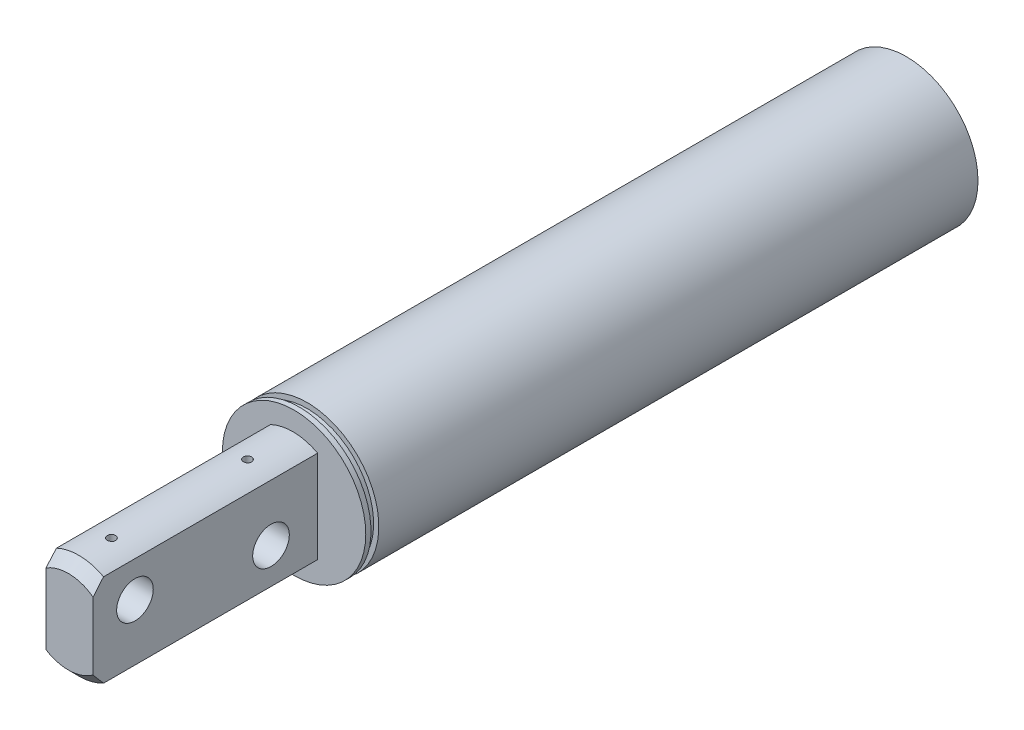
SolidWorks part; units mm, degrees
material "1060 合金"
ref_plane "前视基准面" through (0, 0, 0) normal (0, 0, 1) x (1, 0, 0)
ref_plane "上视基准面" through (0, 0, 0) normal (0, 1, 0) x (1, 0, 0)
ref_plane "右视基准面" through (0, 0, 0) normal (1, 0, 0) x (0, 0, -1)
sketch "草图1" plane through (0, 0, 0) normal (0, 0, 1) x (1, 0, 0)
  circle A0 centre (0, 0) radius 13.7
  dimension "D1" = 27.4
extrude "凸台-拉伸1" add sketch "草图1" along normal blind 117
sketch "草图6" plane through (0, 0, 0) normal (0, 1, 0) x (1, 0, 0)
  line L0 (0, 0) -> (0, -36.1312) construction
  line L1 (-13.7, 0) -> (-13.7, -117) construction
  line L2 (-13.7, -116) -> (-12.7, -116)
  line L3 (-13.7, -116) -> (-13.7, -114.5)
  line L4 (-13.7, -114.5) -> (-12.7, -114.5)
  line L5 (-12.7, -116) -> (-12.7, -114.5)
  line L7 (-13.7, -117) -> (13.7, -117) construction
  dimension "D1" = 1.5
  dimension "D2" = 1
  dimension "D3" = 1
revolve "切除-旋转1" cut sketch "草图6" angle 360 about L0
hole_wizard "M12 螺纹孔1" positions "草图4" profile "草图5" tap size "M12" standard "GB"
sketch "草图4" plane through (0, 0, 0) normal (0, 0, -1) x (-1, 0, 0)
  point P0 (0, 0)
cosmetic thread "孔螺蚊线1" parameters "D1"=26, "D2"=10.4
sketch "草图5" plane through (0, 0, 0) normal (1, 0, 0) x (0, 1, 0)
  line L0 (0, 0) -> (0, 85.3144)
  line L1 (0, 85.3144) -> (5.1, 82.25)
  line L2 (5.1, 82.25) -> (5.1, 0)
  line L5 (5.1, 0) -> (0, 0)
  line L10 (0, 85.3144) -> (-5.1, 82.25) construction
  line L11 (0, -6.35) -> (0, 107.95) construction
  dimension "螺纹孔钻头直径" = 10.2
  dimension "螺纹孔钻头深度" = 82.25
  dimension "导头角度" = 118
sketch "草图9" plane through (0, 0, 117) normal (0, 0, 1) x (1, 0, 0)
  circle A0 centre (-0.2311, 0) radius 10
  dimension "D1" = 20
extrude "凸台-拉伸3" add sketch "草图9" along normal blind 42.91
sketch "草图8" plane through (0, 0, 0) normal (0, 1, 0) x (0, 0, -1)
  line L0 (0, 0) -> (-145.8395, 0) construction
  line L3 (-117, -14.9439) -> (-159.91, -4.5) construction
  line L4 (-117, 4.5) -> (-159.91, 4.5)
  line L5 (-117, 4.5) -> (-117, 14.9439)
  line L6 (-117, 14.9439) -> (-159.91, 14.9439)
  line L7 (-159.91, 4.5) -> (-159.91, 14.9439)
  line L8 (-117, 4.5) -> (-159.91, 14.9439) construction
  line L9 (-117, 14.9439) -> (-159.91, 4.5) construction
  line L11 (-117, -4.5) -> (-159.91, -14.9439) construction
  line L12 (-159.91, -4.5) -> (-159.91, -14.9439)
  line L13 (-117, -14.9439) -> (-159.91, -14.9439)
  line L14 (-117, -4.5) -> (-117, -14.9439)
  line L15 (-117, -4.5) -> (-159.91, -4.5)
  line L16 (-159.91, 10.2311) -> (-159.91, -9.7689) construction
  line L17 (-117, 13.7) -> (-117, -13.7) construction
  point P3 (-138.455, 9.722)
  point P18 (-138.455, -9.722)
  dimension "D1" = 9
extrude "切除-拉伸1" cut sketch "草图8" against normal through all both and the other way through all
chamfer "倒角1" distance 2 angle 45 2 edges at (0.0277, 9.9967, 159.91) (0.0277, -9.9967, 159.91)
hole_wizard "Ø7.0 (7) 直径孔1" positions "草图12" profile "草图11" hole size "Ø7.0" standard "GB" end condition up to next
sketch "草图12" plane through (4.5, 0, 0) normal (1, 0, 0) x (0, 0, -1)
  line L0 (-159.91, 0) -> (-106.462, 0) construction
  line L1 (-159.91, 6.4511) -> (-159.91, -6.4511) construction
  point P0 (-125.91, -2)
  point P2 (-151.91, 2)
  dimension "D1" = 2
  dimension "D2" = 2
  dimension "D3" = 26
  dimension "D4" = 8
sketch "草图11" plane through (4.5, -2, 125.91) normal (0, 1, 0) x (0, 0, -1)
  line L0 (0, 0) -> (0, 9)
  line L1 (0, 9) -> (3.5, 9)
  line L2 (3.5, 9) -> (3.5, 0)
  line L5 (3.5, 0) -> (0, 0)
  line L11 (0, -6.35) -> (0, 107.95) construction
  dimension "通孔孔直径" = 7
  dimension "通孔孔深度" = 9
sketch "草图19" plane through (0, 0, 0) normal (0, 1, 0) x (1, 0, 0)
  line L1 (4.5, -129.41) -> (4.5, -122.41) construction
  line L2 (4.5, -155.41) -> (4.5, -148.41) construction
  line L3 (4.5, -155.41) -> (4.5, -148.41) construction
  line L4 (4.5, -129.41) -> (4.5, -122.41) construction
  line L5 (0, -151.91) -> (4.5, -151.91) construction
  line L6 (0, -125.91) -> (4.5, -125.91) construction
  point P0 (0, -151.91)
  point P1 (0, -125.91)
ref_plane "基准面1" through (0, 10, 0) normal (0, 1, 0) x (1, 0, 0)
hole_wizard "M2 螺纹孔1" positions "草图21" profile "草图20" tap size "M2" standard "GB"
sketch "草图21" plane through (0, 10, 0) normal (0, 1, 0) x (1, 0, 0)
  point P0 (0, -151.91)
  point P2 (0, -125.91)
sketch "草图20" plane through (0, 10, 151.91) normal (1, 0, 0) x (0, 0, 1)
  line L0 (0, 0) -> (0, 4.5)
  line L1 (0, 4.5) -> (0.8, 4.5)
  line L2 (0.8, 4.5) -> (0.8, 0)
  line L5 (0.8, 0) -> (0, 0)
  line L11 (0, -6.35) -> (0, 107.95) construction
  dimension "通孔螺纹孔钻头直径" = 1.6
  dimension "通孔螺纹孔钻头深度" = 4.5
cosmetic thread "孔螺蚊线2" parameters "D2"=2
cosmetic thread "孔螺蚊线3" parameters "D2"=2
